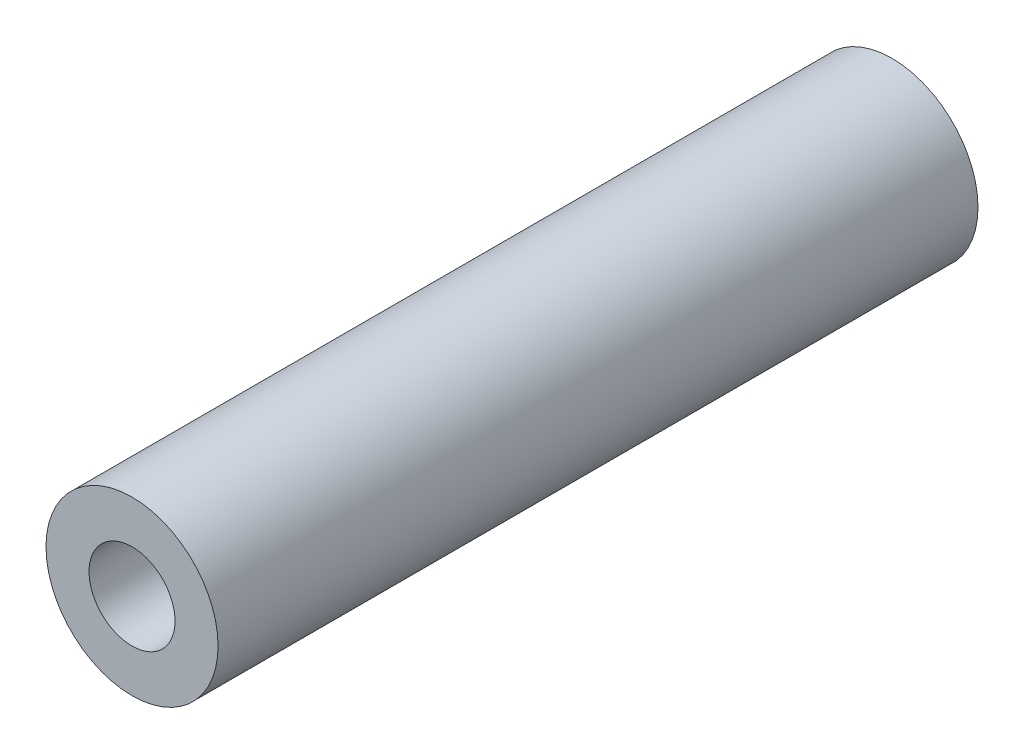
SolidWorks part; units mm, degrees
material "6061 合金"
ref_plane "前视基准面" through (0, 0, 0) normal (0, 0, 1) x (1, 0, 0)
ref_plane "上视基准面" through (0, 0, 0) normal (0, 1, 0) x (1, 0, 0)
ref_plane "右视基准面" through (0, 0, 0) normal (1, 0, 0) x (0, 0, -1)
other "Configuration Table"
sketch "草图1" plane through (0, 0, 0) normal (0, 0, 1) x (1, 0, 0)
  circle A0 centre (0, 0) radius 1.5
  circle A1 centre (0, 0) radius 3
  dimension "D1" = 6
  dimension "D2" = 3
extrude "凸台-拉伸1" add sketch "草图1" along normal blind 26.5
cosmetic thread "装饰螺纹线1" parameters "D2"=5
equation "\"内径\"= 2.5"
equation "\"外径\"= 4"
equation "\"长度\"=26.5"
equation "\"D1@草图1\"=\"外径\""
equation "\"D2@草图1\"=\"内径\""
equation "\"D1@凸台-拉伸1\"=\"长度\""
